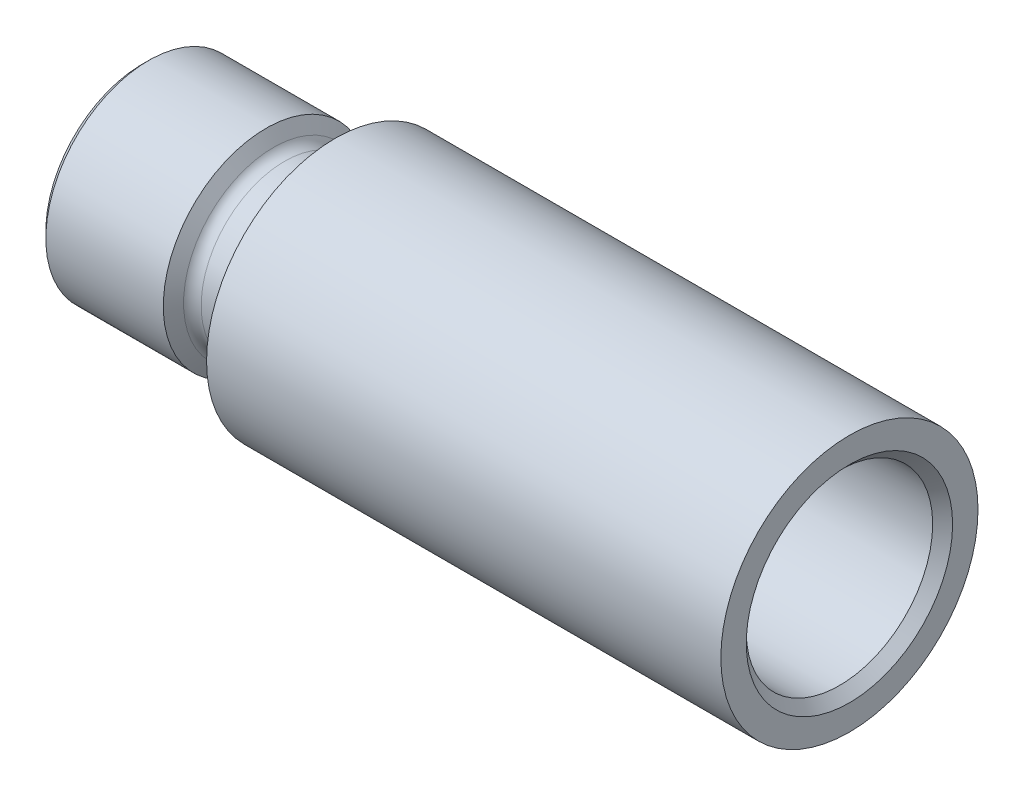
SolidWorks part; units mm, degrees
material "1.0112 (P235S)"
ref_plane "Vorne" through (0, 0, 0) normal (0, 0, 1) x (1, 0, 0)
ref_plane "Oben" through (0, 0, 0) normal (0, 1, 0) x (1, 0, 0)
ref_plane "Rechts" through (0, 0, 0) normal (1, 0, 0) x (0, 0, -1)
sketch "Skizze1" plane through (0, 0, 0) normal (0, 0, 1) x (1, 0, 0)
  line L0 (0, 0) -> (79.8004, 0) construction
  line L1 (55, 4) -> (0, 4)
  line L2 (0, 4) -> (0, 8)
  line L3 (15, 10) -> (55, 10)
  line L4 (55, 10) -> (55, 4)
  line L8 (0, 8) -> (15, 8)
  line L9 (15, 10) -> (15, 8)
  dimension "D1" = 20
  dimension "D2" = 8
  dimension "D3" = 55
  dimension "D4" = 15
  dimension "D5" = 16
revolve "Rotation1" add sketch "Skizze1" angle 360 about L0
cosmetic thread "Gewindedarstellung1" parameters "D1"=15, "D2"=13.55
hole_wizard "M16x1.5 Gewindebohrung1" positions "Skizze3" profile "Skizze2" tap size "M16x1.5" standard "Gabler-Normteile"
sketch "Skizze3" plane through (55, 0, 0) normal (1, 0, 0) x (0, 0, -1)
  point P0 (0, 0)
sketch "Skizze2" plane through (55, 0, 0) normal (0, 1, 0) x (0, 0, -1)
  line L0 (0, 0) -> (0, 31.8562)
  line L1 (0, 31.8562) -> (7.25, 27.5)
  line L2 (7.25, 27.5) -> (7.25, 0.775)
  line L3 (7.25, 0.775) -> (8.025, 0)
  line L5 (8.025, 0) -> (0, 0)
  line L6 (-7.25, 0.775) -> (-8.025, 0) construction
  line L10 (0, 31.8562) -> (-7.25, 27.5) construction
  line L11 (0, -6.35) -> (0, 107.95) construction
  dimension "Bohrerdurchmesser" = 14.5
  dimension "Bohrungstiefe" = 27.5
  dimension "Senkdurchmesser (Oben)" = 16.05
  dimension "Senkwinkel (Oben)" = 90
  dimension "Spitzenwinkel" = 118
cosmetic thread "Bohrungsgewinde1" parameters "D1"=20, "D2"=16
chamfer "Fase1" distance 0.5 angle 45 1 edges at (0, 0, 8)
sketch "Skizze21" plane through (15, 4.8532, 7.617) normal (-1, 0, 0) x (0, 0, 1)
  line L0 (-7.617, 3.1468) -> (-7.617, -4.8532) construction
  line L1 (-7.617, -4.8532) -> (0.383, -4.8532) construction
  circle A0 centre (-7.617, -4.8532) radius 8
  circle A1 centre (-7.617, -4.8532) radius 8 construction
ref_plane "Ebene1" through (15, 0, 0) normal (0, 0, 1) x (1, 0, 0)
sketch "Skizze31" plane through (15, 0, 0) normal (0, 0, 1) x (1, 0, 0)
  line L0 (-5.366, 8) -> (-4.7887, 7)
  line L1 (-3.9226, 6.5) -> (-1, 6.5)
  line L2 (0, 7.5) -> (0, 8)
  line L3 (0, 8) -> (-5.366, 8)
  line L4 (0, 8) -> (0, 0) construction
  line L6 (13.6772, 0) -> (-13.6772, 0) construction
  arc A0 (-1, 6.5) -> (0, 7.5) centre (-1, 7.5) ccw
  arc A1 (-4.7887, 7) -> (-3.9226, 6.5) centre (-3.9226, 7.5) ccw
  point P13 (-4.5, 6.5)
  dimension "r" = 1
  dimension "dg" = 13
  dimension "g1" = 4.5
  dimension "Auslaufwinkel" = 60
revolve "Schnitt-Rotation1" cut sketch "Skizze31" angle 360 about L6
other "DIN 76-1-A<1>"
